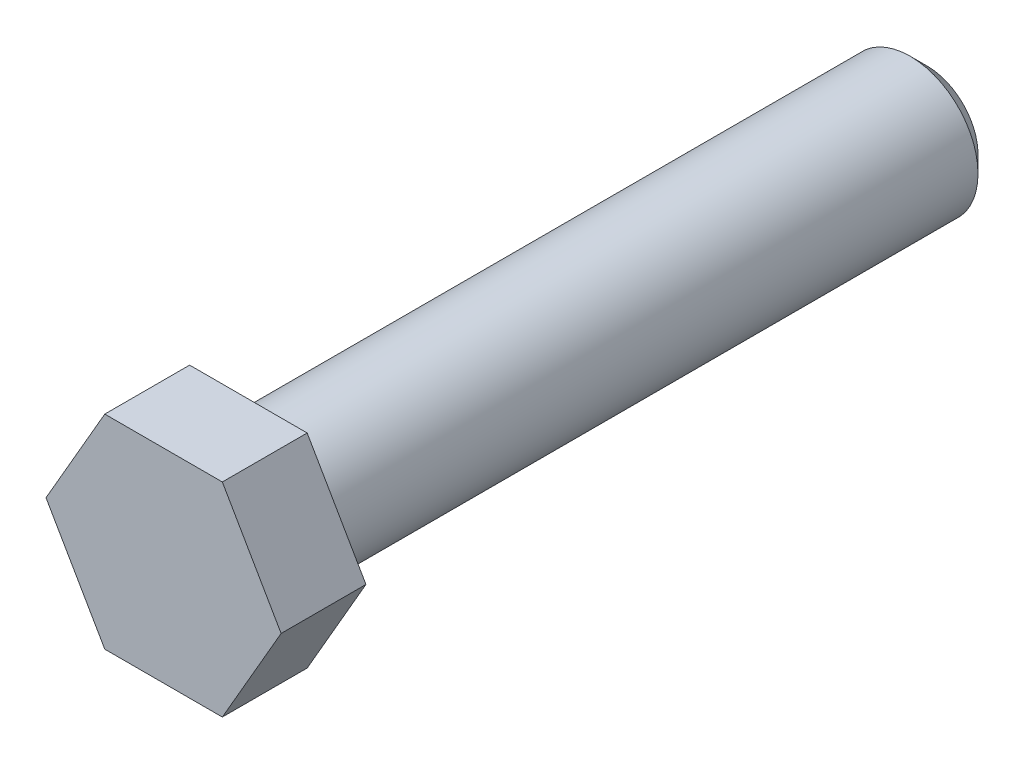
SolidWorks part; units mm, degrees
ref_plane "Plane1" through (0, 0, 0) normal (0, 0, 1) x (1, 0, 0)
ref_plane "MSC_PF1" through (0, 0, 0) normal (0, 1, 0) x (1, 0, 0)
ref_plane "Plane3" through (0, 0, 0) normal (1, 0, 0) x (0, 0, -1)
sketch "Sketch1" plane through (0, 0, 0) normal (0, 0, 1) x (1, 0, 0)
  line L0 (0, 0) -> (1, 0) construction
  line L1 (-5.1962, 9) -> (5.1962, 9)
  line L2 (-5.1962, -9) -> (5.1962, -9)
  line L3 (5.1962, 9) -> (10.3923, 0)
  line L4 (10.3923, 0) -> (5.1962, -9)
  line L5 (-5.1962, 9) -> (-10.3923, 0)
  line L6 (-10.3923, 0) -> (-5.1962, -9)
  circle A0 centre (0, 0) radius 9 construction
  dimension "P" = 1
  dimension "s" = 18
extrude "Base-Extrude" add sketch "Sketch1" along normal blind 7.5
sketch "Sketch3" plane through (0, 0, 0) normal (0, 0, -1) x (-1, 0, 0)
  circle A0 centre (0, 0) radius 6
  dimension "_d" = 12
extrude "Boss-Extrude1" add sketch "Sketch3" along normal blind 60
cosmetic thread "Условное изображение резьбы2" parameters "D2"=11
chamfer "Chamfer1" distance 1.5 angle 45 1 edges at (-6, 0, -60)
